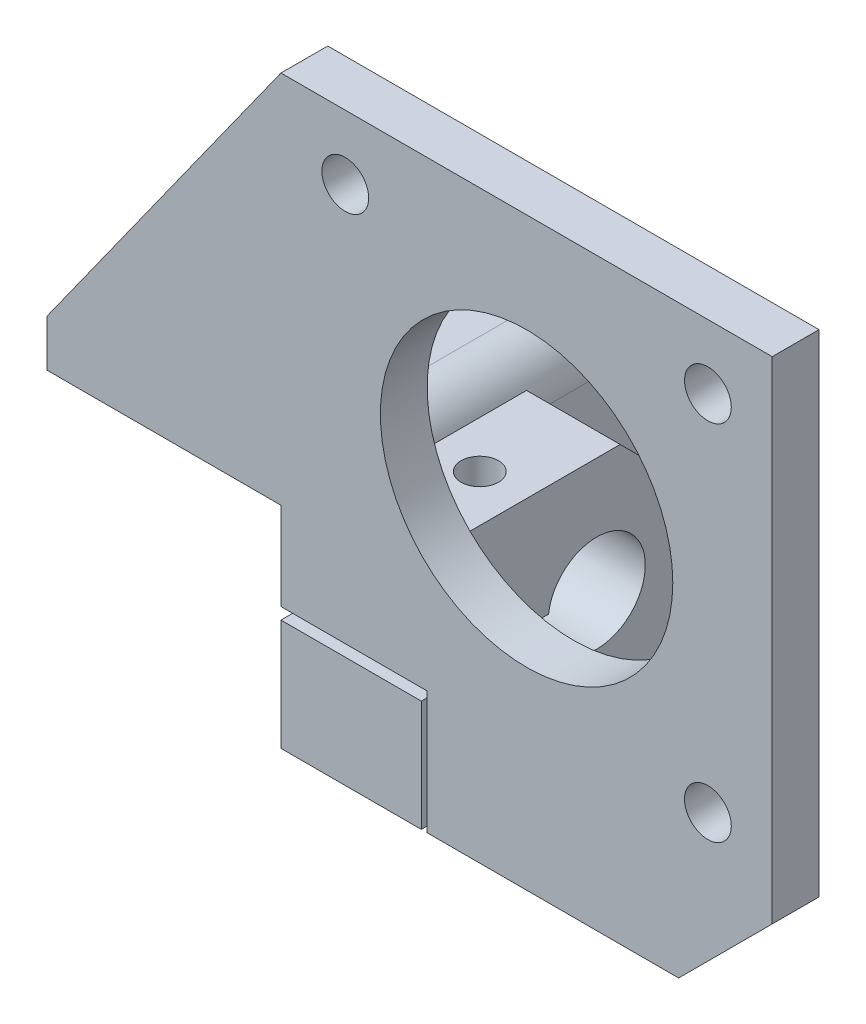
SolidWorks part; units mm, degrees
ref_plane "Plano frontal" through (0, 0, 0) normal (0, 0, 1) x (1, 0, 0)
ref_plane "Plano superior" through (0, 0, 0) normal (0, 1, 0) x (1, 0, 0)
ref_plane "Plano direito" through (0, 0, 0) normal (1, 0, 0) x (0, 0, -1)
sketch "Esboço1" plane through (0, 0, 0) normal (0, 0, 1) x (1, 0, 0)
  line L0 (-21, -11) -> (-41, -11)
  line L1 (-21, 21) -> (21, 21)
  line L2 (-21, -11) -> (-21, -21)
  line L4 (21, 21) -> (21, -21)
  line L5 (-21, 21) -> (21, -21) construction
  line L6 (-21, -21) -> (21, 21) construction
  line L7 (-15.5, 15.5) -> (15.5, 15.5) construction
  line L8 (-15.5, 15.5) -> (-15.5, -15.5) construction
  line L9 (-15.5, -15.5) -> (15.5, -15.5) construction
  line L10 (15.5, 15.5) -> (15.5, -15.5) construction
  line L11 (-15.5, 15.5) -> (15.5, -15.5) construction
  line L12 (-15.5, -15.5) -> (15.5, 15.5) construction
  line L13 (-41, -11) -> (-41, -7)
  line L14 (-21, -21) -> (-21, -29)
  line L15 (-21, -29) -> (13, -29)
  line L16 (13, -29) -> (21, -21)
  line L17 (-41, -7) -> (-21, 21)
  circle A0 centre (-15.5, 15.5) radius 2
  circle A1 centre (15.5, 15.5) radius 2
  circle A2 centre (15.5, -15.5) radius 2
  circle A3 centre (0, 0) radius 12.5
  point P0 (0, 0)
  point P6 (0, 0)
  dimension "D2" = 4
  dimension "D5" = 25
  dimension "D1" = 31
  dimension "D3" = 42
  dimension "D4" = 42
  dimension "D6" = 45
  dimension "D7" = 20
  dimension "D8" = 8
  dimension "D9" = 4
  dimension "D10" = 10
extrude "Ressalto-extrusão1" add sketch "Esboço1" along normal blind 4
sketch "Esboço2" plane through (0, 0, 0) normal (0, 0, -1) x (-1, 0, 0)
  line L0 (41, -11) -> (41, -7)
  line L1 (41, -7) -> (21, -7)
  line L2 (17, -11) -> (17, -29)
  line L3 (21, -29) -> (-13, -29) construction
  line L4 (17, -29) -> (21, -29)
  line L5 (21, -29) -> (21, -11)
  line L6 (21, -11) -> (41, -11)
  arc A0 (21, -7) -> (17, -11) centre (21, -11) ccw
  dimension "D1" = 4
extrude "Ressalto-extrusão2" add sketch "Esboço2" along normal blind 25
sketch "Esboço3" plane through (-17, 0, 0) normal (1, 0, 0) x (0, 0, -1)
  line L0 (0, -9) -> (13, -9)
  line L1 (0, -11) -> (0, -29) construction
  line L2 (13, -9) -> (18, -14)
  line L3 (18, -14) -> (18, -24)
  line L4 (18, -24) -> (13, -29)
  line L5 (25, -29) -> (0, -29) construction
  line L6 (13, -29) -> (0, -29)
  line L7 (0, -29) -> (0, -9)
  line L8 (-4, -29) -> (-4, -21) construction
  line L9 (13, -9) -> (13, -29) construction
  circle A0 centre (11, -19) radius 4.15
  point P6 (18, -19)
  dimension "D1" = 8.3
  dimension "D2" = 15
  dimension "D3" = 20
  dimension "D4" = 10
  dimension "D5" = 2
extrude "Ressalto-extrusão3" add sketch "Esboço3" along normal blind 8
sketch "Esboço4" plane through (0, 0, 0) normal (0, 0, -1) x (-1, 0, 0)
  line L0 (8.5, -18.5) -> (21.5, -18.5)
  line L3 (21.5, -18.5) -> (21.5, -26)
  line L4 (21.5, -26) -> (21, -29)
  line L5 (9, -29) -> (17, -29) construction
  line L6 (21, -29) -> (21, -19.5)
  line L7 (21, -19.5) -> (9, -19.5)
  line L8 (9, -19.5) -> (9, -29)
  line L9 (9, -29) -> (8.5, -29)
  line L10 (8.5, -29) -> (8.5, -18.5)
  dimension "D1" = 10.5
  dimension "D2" = 1
  dimension "D3" = 0.5
  dimension "D4" = 0.5
extrude "Corte-extrusão1" cut sketch "Esboço4" against normal blind 8 and the other way blind 8
sketch "Esboço5" plane through (-17, 0, 0) normal (1, 0, 0) x (0, 0, -1)
  line L0 (25, -11) -> (15, -11) construction
  line L1 (25, -29) -> (25, -11) construction
  circle A0 centre (21, -21) radius 1.75
  circle A2 centre (11, -19) radius 4.15
  dimension "D3" = 3.5
  dimension "D1" = 10
  dimension "D2" = 4
extrude "Corte-extrusão2" cut sketch "Esboço5" against normal blind 12
sketch "Esboço6" plane through (0, -7, 0) normal (0, 1, 0) x (1, 0, 0)
  line L0 (-21, 25) -> (-21, 0) construction
  line L1 (-41, 25) -> (-21, 25) construction
  circle A0 centre (-31.5, 18) radius 1.75
  circle A1 centre (-31.5, -2) radius 1.75
  dimension "D2" = 3.5
  dimension "D1" = 20
  dimension "D3" = 10.5
  dimension "D4" = 7
extrude "Corte-extrusão3" cut sketch "Esboço6" against normal blind 12
sketch "Esboço7" plane through (0, -29, 0) normal (0, -1, 0) x (1, 0, 0)
  line L0 (-9, -13) -> (-17, -13) construction
  line L2 (-8.5, 0) -> (13, 0) construction
  circle A0 centre (-13, -5) radius 1.6
  point P5 (-13, -13)
  dimension "D2" = 3.2
  dimension "D1" = 5
extrude "Corte-extrusão4" cut sketch "Esboço7" against normal through all
